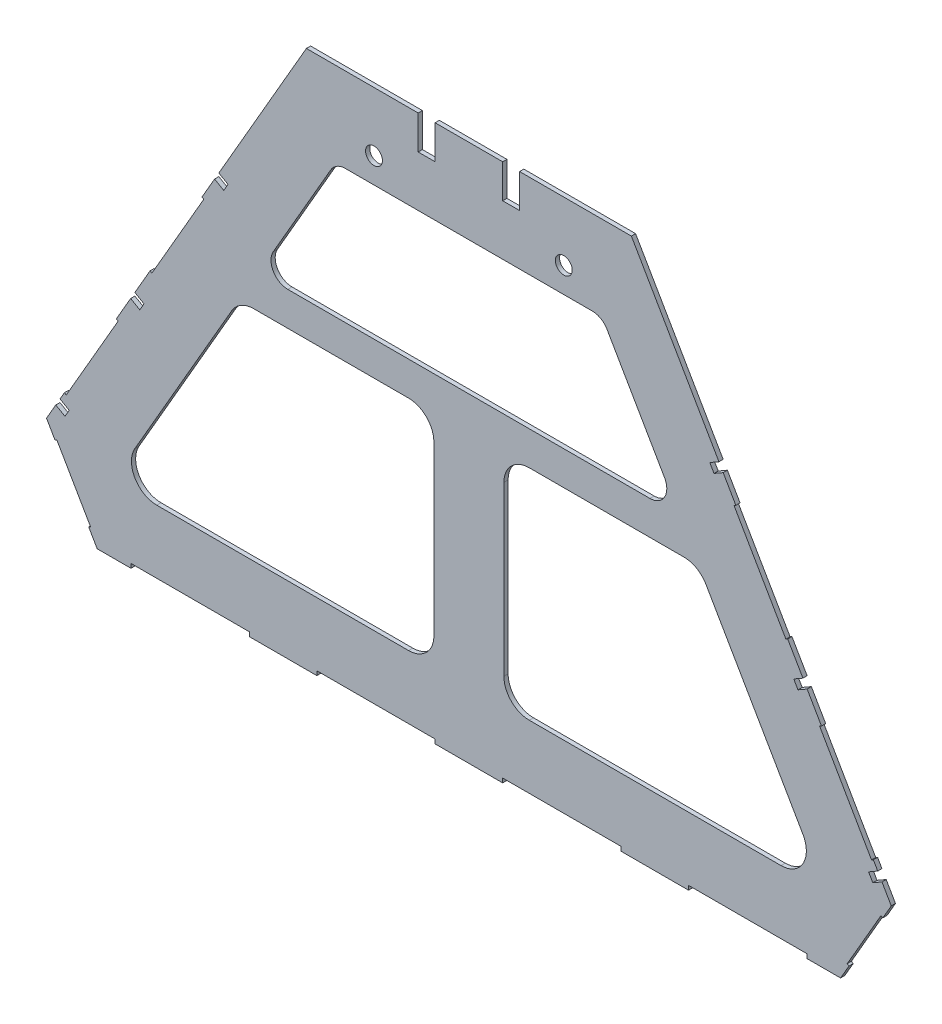
SolidWorks part; units mm, degrees
material "Teak"
ref_plane "Front Plane" through (0, 0, 0) normal (0, 0, 1) x (1, 0, 0)
ref_plane "Top Plane" through (0, 0, 0) normal (0, 1, 0) x (1, 0, 0)
ref_plane "Right Plane" through (0, 0, 0) normal (1, 0, 0) x (0, 0, -1)
sketch "Sketch7" plane through (0, 0, 0) normal (0, 0, 1) x (1, 0, 0)
  line L0 (0, 0) -> (0, 167.2619) construction
  line L1 (279.4, 0) -> (-279.4, 0)
  line L2 (-279.4, 0) -> (-317.5, 65.9911)
  line L3 (-317.5, 65.9911) -> (-122.138, 404.368)
  line L4 (-122.138, 404.368) -> (122.138, 404.368)
  line L6 (317.5, 65.9911) -> (122.138, 404.368)
  line L7 (279.4, 0) -> (317.5, 65.9911)
  point P1 (0, 0)
  dimension "D1" = 558.8
  dimension "D2" = 76.2
  dimension "D3" = 404.368
  dimension "D4" = 60
  dimension "D5" = 60
extrude "Boss-Extrude1" add sketch "Sketch7" along normal blind 3.175
sketch "Sketch8" plane through (0, 0, 3.175) normal (0, 0, 1) x (1, 0, 0)
  line L0 (-38.1, 404.368) -> (-38.1, 378.968)
  line L1 (122.138, 404.368) -> (-122.138, 404.368) construction
  line L2 (-38.1, 378.968) -> (-25.4, 378.968)
  line L3 (-25.4, 378.968) -> (-25.4, 404.368)
  line L4 (-25.4, 404.368) -> (-38.1, 404.368)
  line L5 (0, -595.632) -> (0, 49404.368) construction
  line L10 (38.1, 404.368) -> (25.4, 404.368)
  line L11 (38.1, 404.368) -> (38.1, 378.968)
  line L12 (38.1, 378.968) -> (25.4, 378.968)
  line L13 (25.4, 404.368) -> (25.4, 378.968)
  point P14 (0, 404.368)
  dimension "D1" = 50.8
  dimension "D2" = 25.4
  dimension "D3" = 12.7
  dimension "D4" = 25.4
  dimension "D5" = 25.4
  dimension "D6" = 12.7
extrude "Cut-Extrude1" cut sketch "Sketch8" against normal through all
sketch "Sketch9" plane through (0, 0, 3.175) normal (0, 0, 1) x (1, 0, 0)
  line L0 (-279.4, 0) -> (279.4, 0) construction
  line L1 (-254, 0) -> (-165.1, 0)
  line L2 (-254, 0) -> (-254, 3.175)
  line L3 (-254, 3.175) -> (-165.1, 3.175)
  line L4 (-165.1, 0) -> (-165.1, 3.175)
  line L5 (-114.3, 3.175) -> (-25.4, 3.175)
  line L6 (-114.3, 0) -> (-114.3, 3.175)
  line L7 (-114.3, 0) -> (-25.4, 0)
  line L8 (-25.4, 0) -> (-25.4, 3.175)
  line L9 (25.4, 3.175) -> (114.3, 3.175)
  line L10 (25.4, 0) -> (25.4, 3.175)
  line L11 (25.4, 0) -> (114.3, 0)
  line L12 (114.3, 0) -> (114.3, 3.175)
  line L13 (165.1, 3.175) -> (254, 3.175)
  line L14 (165.1, 0) -> (165.1, 3.175)
  line L15 (165.1, 0) -> (254, 0)
  line L16 (254, 0) -> (254, 3.175)
  dimension "D1" = 25.4
  dimension "D2" = 88.9
  dimension "D3" = 3.175
  dimension "D5" = 50.8
  dimension "D4" = 4
extrude "Cut-Extrude2" cut sketch "Sketch9" against normal through all
sketch "Sketch10" plane through (0, 0, 3.175) normal (0, 0, 1) x (1, 0, 0)
  line L0 (-311.15, 54.9926) -> (-309.7752, 55.7864)
  line L1 (-317.5, 65.9911) -> (-279.4, 0) construction
  line L2 (-309.7752, 55.7864) -> (-284.3752, 11.7923)
  line L3 (-284.3752, 11.7923) -> (-285.75, 10.9985)
  line L4 (-285.75, 10.9985) -> (-311.15, 54.9926)
  line L5 (0, -494.068) -> (0, 49505.932) construction
  line L6 (25.4, 404.368) -> (-25.4, 404.368) construction
  line L7 (285.75, 10.9985) -> (311.15, 54.9926)
  line L8 (284.3752, 11.7923) -> (285.75, 10.9985)
  line L9 (309.7752, 55.7864) -> (284.3752, 11.7923)
  line L10 (311.15, 54.9926) -> (309.7752, 55.7864)
  point P13 (0, 404.368)
  dimension "D1" = 1.5875
  dimension "D2" = 12.7
  dimension "D3" = 12.7
extrude "Cut-Extrude3" cut sketch "Sketch10" against normal through all
sketch "Sketch11" plane through (0, 0, 3.175) normal (0, 0, 1) x (1, 0, 0)
  line L0 (-304.038, 89.308) -> (-302.6632, 88.5143)
  line L1 (-122.138, 404.368) -> (-317.5, 65.9911) construction
  line L2 (-302.6632, 88.5143) -> (-263.6742, 156.0452)
  line L3 (-263.6742, 156.0452) -> (-265.049, 156.8389)
  line L4 (-265.049, 156.8389) -> (-304.038, 89.308)
  line L5 (-238.2742, 200.0393) -> (-199.2852, 267.5702)
  line L6 (-199.2852, 267.5702) -> (-200.66, 268.364)
  line L7 (-200.66, 268.364) -> (-239.649, 200.833)
  line L8 (-239.649, 200.833) -> (-238.2742, 200.0393)
  line L9 (0, -494.068) -> (0, 49505.932) construction
  line L10 (25.4, 404.368) -> (-25.4, 404.368) construction
  line L11 (304.038, 89.308) -> (302.6632, 88.5143)
  line L12 (263.6742, 156.0452) -> (265.049, 156.8389)
  line L13 (265.049, 156.8389) -> (304.038, 89.308)
  line L14 (302.6632, 88.5143) -> (263.6742, 156.0452)
  line L15 (239.649, 200.833) -> (238.2742, 200.0393)
  line L16 (199.2852, 267.5702) -> (200.66, 268.364)
  line L17 (200.66, 268.364) -> (239.649, 200.833)
  line L18 (238.2742, 200.0393) -> (199.2852, 267.5702)
  point P16 (0, 404.368)
  dimension "D1" = 26.924
  dimension "D2" = 77.978
  dimension "D3" = 1.5875
  dimension "D5" = 50.8
  dimension "D4" = 2
extrude "Cut-Extrude4" cut sketch "Sketch11" against normal through all
sketch "Sketch12" plane through (0, 0, 3.175) normal (0, 0, 1) x (1, 0, 0)
  line L0 (-254.254, 175.5364) -> (-247.3799, 171.5677)
  line L1 (-239.649, 200.833) -> (-265.049, 156.8389) construction
  line L2 (-247.3799, 171.5677) -> (-244.2049, 177.0669)
  line L3 (-244.2049, 177.0669) -> (-251.079, 181.0357)
  line L4 (-251.079, 181.0357) -> (-254.254, 175.5364)
  line L5 (-263.6742, 156.0452) -> (-265.049, 156.8389) construction
  line L6 (0, -494.068) -> (0, 49505.932) construction
  line L7 (25.4, 404.368) -> (-25.4, 404.368) construction
  line L8 (251.079, 181.0357) -> (254.254, 175.5364)
  line L9 (244.2049, 177.0669) -> (251.079, 181.0357)
  line L10 (247.3799, 171.5677) -> (244.2049, 177.0669)
  line L11 (254.254, 175.5364) -> (247.3799, 171.5677)
  line L12 (-310.515, 78.0895) -> (-303.6409, 74.1208)
  line L13 (-303.6409, 74.1208) -> (-300.4659, 79.62)
  line L14 (-300.4659, 79.62) -> (-307.34, 83.5888)
  line L15 (-307.34, 83.5888) -> (-310.515, 78.0895)
  line L16 (-191.135, 284.8617) -> (-184.2609, 280.893)
  line L17 (-184.2609, 280.893) -> (-181.0859, 286.3922)
  line L18 (-181.0859, 286.3922) -> (-187.96, 290.361)
  line L19 (-187.96, 290.361) -> (-191.135, 284.8617)
  line L21 (307.34, 83.5888) -> (310.515, 78.0895)
  line L22 (300.4659, 79.62) -> (307.34, 83.5888)
  line L23 (303.6409, 74.1208) -> (300.4659, 79.62)
  line L24 (310.515, 78.0895) -> (303.6409, 74.1208)
  line L25 (187.96, 290.361) -> (191.135, 284.8617)
  line L26 (181.0859, 286.3922) -> (187.96, 290.361)
  line L27 (184.2609, 280.893) -> (181.0859, 286.3922)
  line L28 (191.135, 284.8617) -> (184.2609, 280.893)
  point P8 (-264.3616, 156.4421)
  point P14 (0, 404.368)
  dimension "D1" = 6.35
  dimension "D2" = 7.9375
  dimension "D3" = 21.59
  dimension "D5" = 13.97
  dimension "D7" = 19.05
  dimension "D4" = 2
  dimension "D6" = 2
extrude "Cut-Extrude5" cut sketch "Sketch12" against normal through all
sketch "Sketch13" plane through (0, 0, 3.175) normal (0, 0, 1) x (1, 0, 0)
  line L0 (-92.8086, 340.868) -> (92.8086, 340.868)
  line L1 (103.8072, 334.518) -> (147.068, 259.588)
  line L2 (136.0695, 240.538) -> (-136.0695, 240.538)
  line L3 (-147.068, 259.588) -> (-103.8072, 334.518)
  line L4 (-25.4, 0) -> (25.4, 0) construction
  line L5 (25.4, 404.368) -> (-25.4, 404.368) construction
  line L6 (200.66, 268.364) -> (191.135, 284.8617) construction
  line L7 (-122.138, 404.368) -> (-187.96, 290.361) construction
  arc A0 (147.068, 259.588) -> (136.0695, 240.538) centre (136.0695, 253.238) cw
  arc A1 (92.8086, 340.868) -> (103.8072, 334.518) centre (92.8086, 328.168) cw
  arc A2 (-92.8086, 340.868) -> (-103.8072, 334.518) centre (-92.8086, 328.168) ccw
  arc A3 (-136.0695, 240.538) -> (-147.068, 259.588) centre (-136.0695, 253.238) cw
  dimension "D5" = 12.7
  dimension "D1" = 240.538
  dimension "D2" = 63.5
  dimension "D3" = 50.8
  dimension "D4" = 50.8
extrude "Cut-Extrude6" cut sketch "Sketch13" against normal through all
sketch "Sketch14" plane through (0, 0, 3.175) normal (0, 0, 1) x (1, 0, 0)
  line L0 (0, -1000) -> (0, 49000) construction
  line L1 (45.3618, 215.138) -> (161.7327, 215.138)
  line L2 (178.2305, 205.613) -> (251.114, 79.375)
  line L3 (234.6163, 50.8) -> (45.3618, 50.8)
  line L5 (114.3, 0) -> (165.1, 0) construction
  line L6 (-161.7327, 215.138) -> (-45.3618, 215.138)
  line L7 (263.6742, 156.0452) -> (302.6632, 88.5143) construction
  line L8 (251.079, 181.0357) -> (239.649, 200.833) construction
  line L9 (-136.0695, 240.538) -> (136.0695, 240.538) construction
  line L12 (-178.2305, 205.613) -> (-251.114, 79.375)
  line L14 (-26.3118, 196.088) -> (-26.3118, 69.85)
  line L15 (-45.3618, 50.8) -> (-234.6163, 50.8)
  line L16 (26.3118, 196.088) -> (26.3118, 69.85)
  arc A1 (251.114, 79.375) -> (234.6163, 50.8) centre (234.6163, 69.85) cw
  arc A2 (161.7327, 215.138) -> (178.2305, 205.613) centre (161.7327, 196.088) cw
  arc A5 (-161.7327, 215.138) -> (-178.2305, 205.613) centre (-161.7327, 196.088) ccw
  arc A6 (-251.114, 79.375) -> (-234.6163, 50.8) centre (-234.6163, 69.85) ccw
  arc A8 (-26.3118, 69.85) -> (-45.3618, 50.8) centre (-45.3618, 69.85) cw
  arc A9 (-45.3618, 215.138) -> (-26.3118, 196.088) centre (-45.3618, 196.088) cw
  arc A10 (45.3618, 50.8) -> (26.3118, 69.85) centre (45.3618, 69.85) cw
  arc A11 (45.3618, 215.138) -> (26.3118, 196.088) centre (45.3618, 196.088) ccw
  point P9 (139.7, 0)
  point P11 (-26.3118, 50.8)
  point P21 (26.3118, 50.8)
  point P24 (267.6118, 50.8)
  point P30 (26.3118, 50.8)
  point P40 (26.3118, 215.138)
  point P41 (-267.6118, 50.8)
  point P42 (-26.3118, 50.8)
  dimension "D5" = 19.05
  dimension "D6" = 19.05
  dimension "D1" = 50.8
  dimension "D2" = 50.8
  dimension "D3" = 25.4
  dimension "D4" = 241.3
extrude "Cut-Extrude7" cut sketch "Sketch14" against normal through all
sketch "Sketch15" plane through (0, 0, 0) normal (0, 0, -1) x (-1, 0, 0)
  line L0 (-25.4, 404.368) -> (25.4, 404.368) construction
  line L2 (0, -595.632) -> (0, 49404.368) construction
  circle A0 centre (-71.338, 359.918) radius 6.35
  circle A2 centre (71.338, 359.918) radius 6.35
  point P7 (0, 404.368)
  dimension "D1" = 12.7
  dimension "D5" = 50.8
  dimension "D4" = 44.45
extrude "Cut-Extrude8" cut sketch "Sketch15" against normal through all
